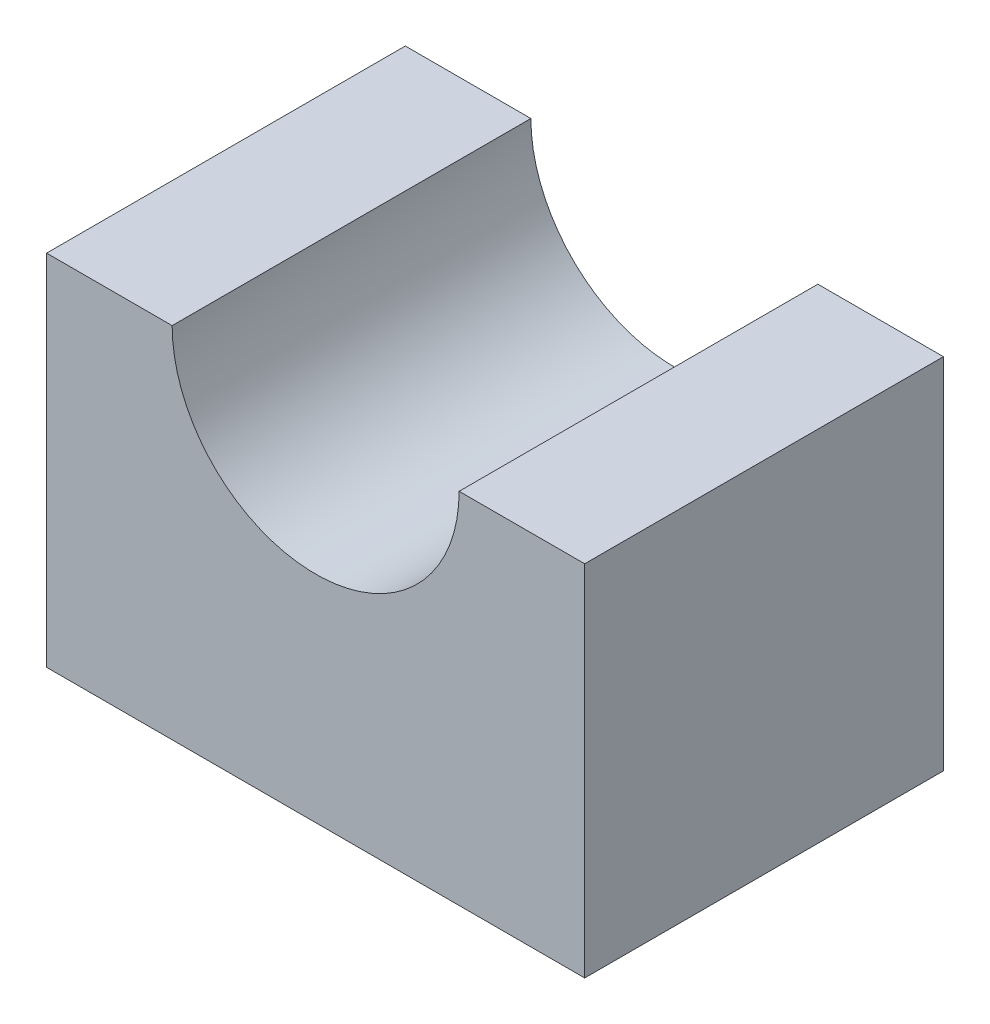
SolidWorks part; units mm, degrees
ref_plane "Front Plane" through (0, 0, 0) normal (0, 0, 1) x (1, 0, 0)
ref_plane "Top Plane" through (0, 0, 0) normal (0, 1, 0) x (1, 0, 0)
ref_plane "Right Plane" through (0, 0, 0) normal (1, 0, 0) x (0, 0, -1)
sketch "Sketch1" plane through (0, 0, 0) normal (0, 0, 1) x (1, 0, 0)
  line L0 (8, 0) -> (15, 0)
  line L1 (-15, 0) -> (-8, 0)
  line L2 (-15, 0) -> (-15, -20)
  line L3 (-15, -20) -> (15, -20)
  line L4 (15, 0) -> (15, -20)
  arc A0 (-8, 0) -> (8, 0) centre (0, 0) ccw
  point P1 (0, 0)
  point P7 (0, -20)
  dimension "D1" = 16
  dimension "D2" = 20
  dimension "D3" = 30
extrude "Boss-Extrude1" add sketch "Sketch1" along normal mid plane 20
